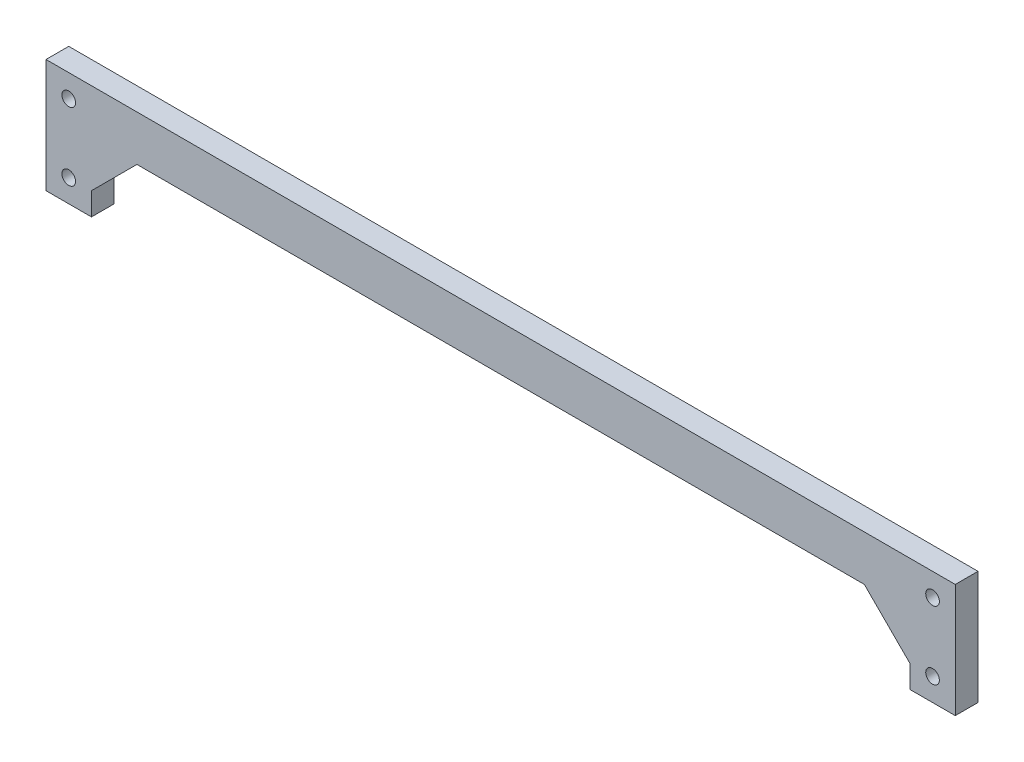
SolidWorks part; units mm, degrees
material "Perspex (TM) GS Acrylic Cast Sheet"
ref_plane "Front Plane" through (0, 0, 0) normal (0, 0, 1) x (1, 0, 0)
ref_plane "Top Plane" through (0, 0, 0) normal (0, 1, 0) x (1, 0, 0)
ref_plane "Right Plane" through (0, 0, 0) normal (1, 0, 0) x (0, 0, -1)
sketch "Sketch1" plane through (0, 0, 0) normal (0, 0, 1) x (1, 0, 0)
  line L0 (0, 0) -> (0, -25)
  line L1 (0, -55) -> (0, 55) construction
  line L2 (10, -20) -> (10, -25)
  line L3 (10, -20) -> (20, -10)
  line L4 (20, -10) -> (100, -10)
  line L5 (100, -10) -> (100, 0)
  line L6 (55, 0) -> (-55, 0) construction
  line L7 (100, 0) -> (0, 0)
  line L8 (10, -25) -> (0, -25)
  circle A0 centre (5, -20) radius 1.5
  circle A1 centre (5, -5) radius 1.5
  dimension "D6" = 3
  dimension "D7" = 5
  dimension "D9" = 5
  dimension "D10" = 5
  dimension "D1" = 100
  dimension "D2" = 25
  dimension "D3" = 10
  dimension "D4" = 10
  dimension "D5" = 45
  dimension "D8" = 5
extrude "Boss-Extrude1" add sketch "Sketch1" along normal blind 5
mirror "Mirror1" about plane through (100, -10, 5) normal (-1, 0, 0) of bodies 101
